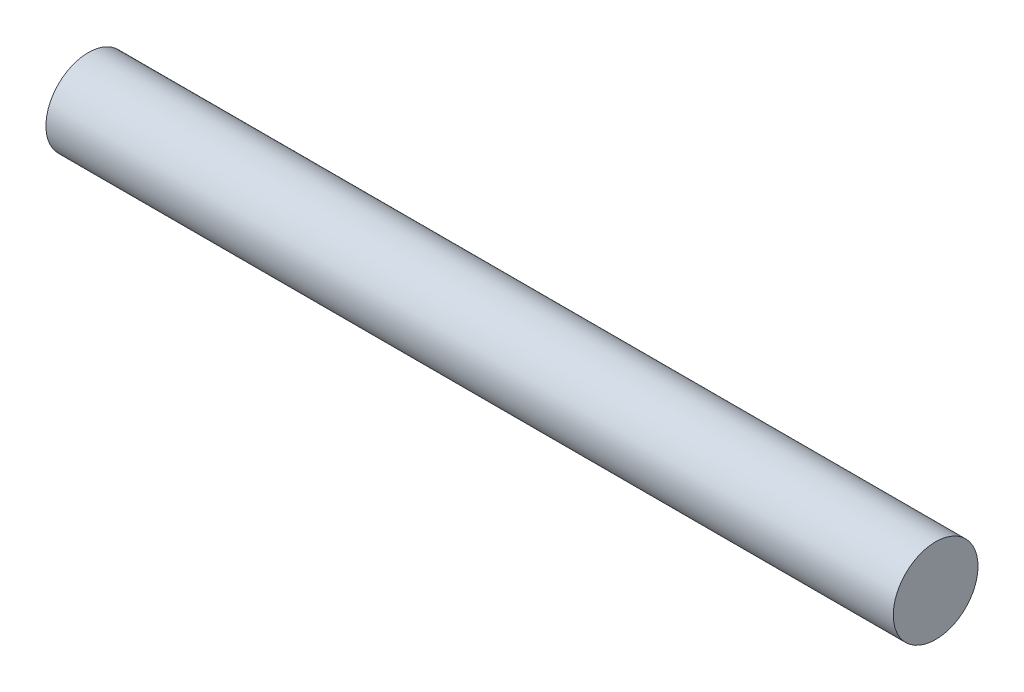
SolidWorks part; units mm, degrees
ref_plane "Front Plane" through (0, 0, 0) normal (0, 0, 1) x (1, 0, 0)
ref_plane "Top Plane" through (0, 0, 0) normal (0, 1, 0) x (1, 0, 0)
ref_plane "Right Plane" through (0, 0, 0) normal (1, 0, 0) x (0, 0, -1)
sketch "Sketch1" plane through (0, 0, 0) normal (1, 0, 0) x (0, 0, -1)
  circle A0 centre (0, 0) radius 1
  dimension "D1" = 2
extrude "Boss-Extrude1" add sketch "Sketch1" along normal blind 20
sketch "Sketch2" plane through (20, 0, 0) normal (1, 0, 0) x (0, 0, -1)
  circle A1 centre (0, 0) radius 1
  circle A2 centre (0, 0) radius 1
  dimension "D1" = 0
